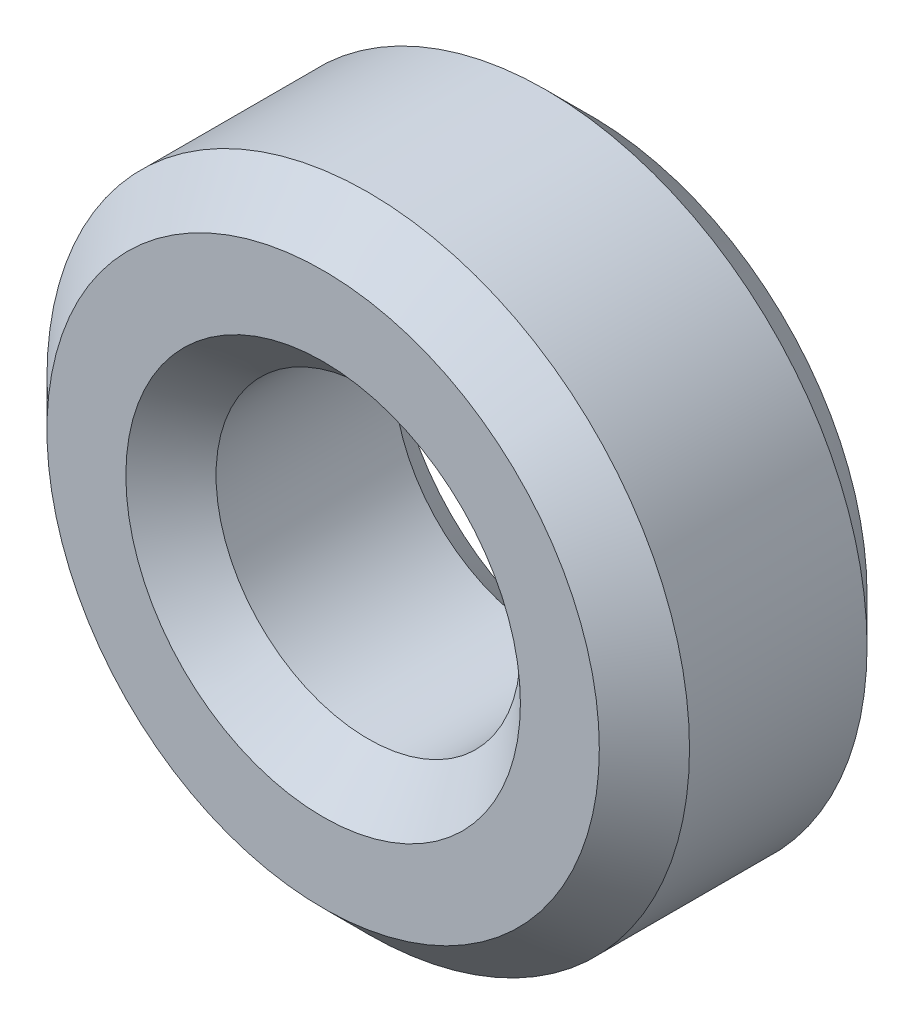
SolidWorks part; units mm, degrees
ref_plane "Plano frontal" through (0, 0, 0) normal (0, 0, 1) x (1, 0, 0)
ref_plane "Plano superior" through (0, 0, 0) normal (0, 1, 0) x (1, 0, 0)
ref_plane "Plano direito" through (0, 0, 0) normal (1, 0, 0) x (0, 0, -1)
sketch "Esboço1" plane through (0, 0, 0) normal (0, 0, 1) x (1, 0, 0)
  circle A0 centre (0, 0) radius 5.7
  circle A1 centre (0, 0) radius 2.7
  dimension "D1" = 5.4
  dimension "D2" = 3
extrude "Ressalto-extrusão1" add sketch "Esboço1" along normal blind 4.75
chamfer "Chanfro1" distance 0.8 angle 45 4 edges at (2.7, 0, 0) (5.7, 0, 0) (2.7, 0, 4.75) (5.7, 0, 4.75)
